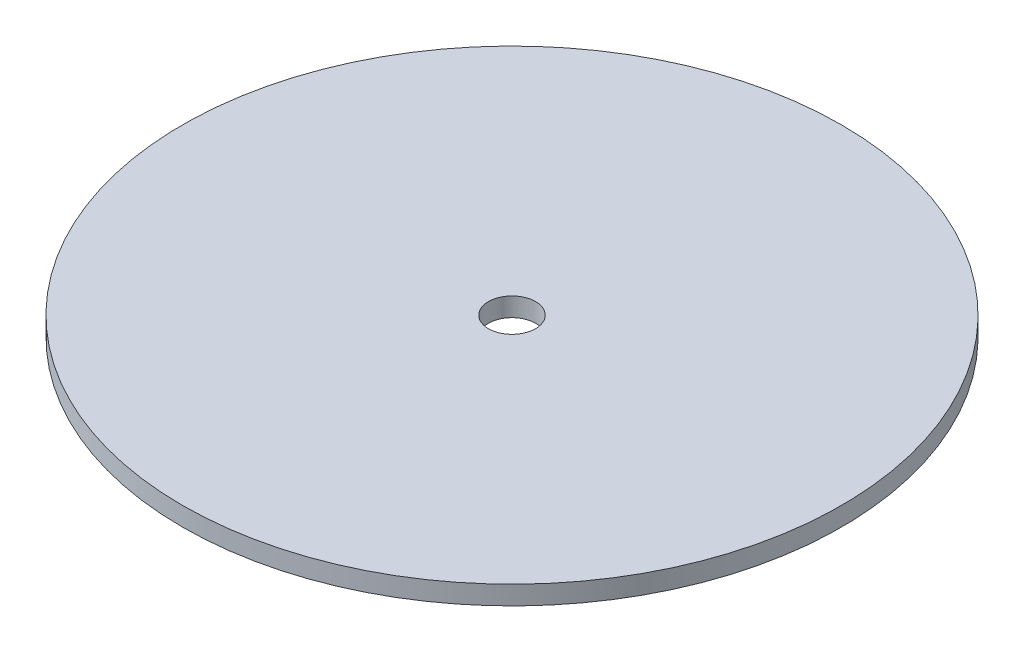
SolidWorks part; units mm, degrees
ref_plane "Front Plane" through (0, 0, 0) normal (0, 0, 1) x (1, 0, 0)
ref_plane "Top Plane" through (0, 0, 0) normal (0, 1, 0) x (1, 0, 0)
ref_plane "Right Plane" through (0, 0, 0) normal (1, 0, 0) x (0, 0, -1)
sketch "Sketch1" plane through (0, 0, 0) normal (0, 1, 0) x (1, 0, 0)
  circle A0 centre (0, 0) radius 140
  circle A1 centre (0, 0) radius 10
  dimension "D1" = 280
  dimension "D2" = 20
extrude "Boss-Extrude1" add sketch "Sketch1" along normal blind 8
